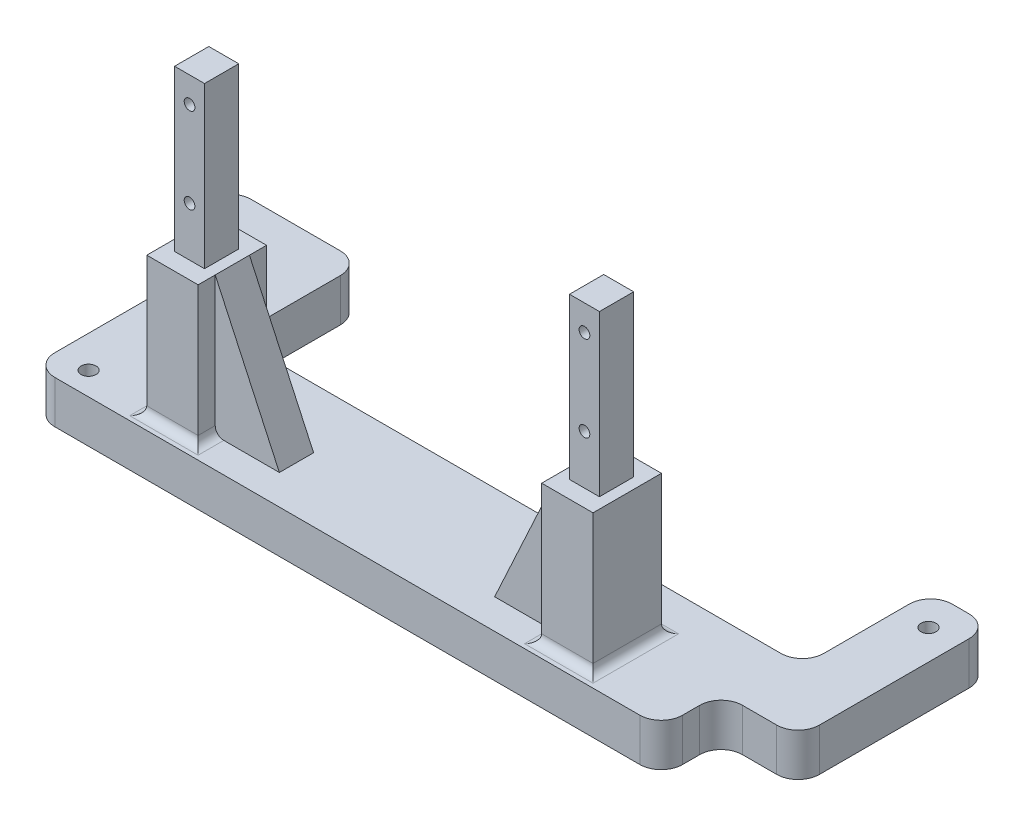
SolidWorks part; units mm, degrees
ref_plane "Front Plane" through (0, 0, 0) normal (0, 0, 1) x (1, 0, 0)
ref_plane "Top Plane" through (0, 0, 0) normal (0, 1, 0) x (1, 0, 0)
ref_plane "Right Plane" through (0, 0, 0) normal (1, 0, 0) x (0, 0, -1)
sketch "Sketch1" plane through (0, 0, 0) normal (0, 1, 0) x (1, 0, 0)
  line L0 (-7.5, -0.4) -> (-7.5, 38.6)
  line L1 (-7.5, 38.6) -> (-15.61, 38.6)
  line L2 (-20.61, 43.6) -> (-20.61, 48.6)
  line L4 (157.26, 48.6) -> (157.26, 13.6)
  line L14 (139.26, 3.6) -> (139.26, -0.4)
  line L18 (144.26, 8.6) -> (152.26, 8.6)
  line L20 (-2.5, -5.4) -> (134.26, -5.4)
  line L21 (-15.61, 53.6) -> (5.26, 53.6)
  line L22 (10.26, 48.6) -> (10.26, 28.6)
  line L23 (15.26, 23.6) -> (138.26, 23.6)
  line L24 (143.26, 28.6) -> (143.26, 48.6)
  line L25 (148.26, 53.6) -> (152.26, 53.6)
  circle A0 centre (0, 0) radius 1.75
  circle A1 centre (-14.61, 46.1) radius 1.75
  circle A3 centre (150.26, 46.1) radius 1.75
  arc A4 (138.26, 23.6) -> (143.26, 28.6) centre (138.26, 28.6) ccw
  arc A5 (143.26, 48.6) -> (148.26, 53.6) centre (148.26, 48.6) cw
  arc A6 (152.26, 53.6) -> (157.26, 48.6) centre (152.26, 48.6) cw
  arc A7 (157.26, 13.6) -> (152.26, 8.6) centre (152.26, 13.6) cw
  arc A8 (144.26, 8.6) -> (139.26, 3.6) centre (144.26, 3.6) ccw
  arc A9 (139.26, -0.4) -> (134.26, -5.4) centre (134.26, -0.4) cw
  arc A10 (-2.5, -5.4) -> (-7.5, -0.4) centre (-2.5, -0.4) cw
  arc A11 (15.26, 23.6) -> (10.26, 28.6) centre (15.26, 28.6) cw
  arc A12 (10.26, 48.6) -> (5.26, 53.6) centre (5.26, 48.6) ccw
  arc A13 (-20.61, 43.6) -> (-15.61, 38.6) centre (-15.61, 43.6) ccw
  arc A14 (-15.61, 53.6) -> (-20.61, 48.6) centre (-15.61, 48.6) ccw
  point P23 (-20.61, 46.1)
  point P27 (157.26, 8.6)
  point P32 (139.26, 8.6)
  point P43 (-20.61, 38.6)
  point P46 (-20.61, 53.6)
  dimension "D5" = 3.5
  dimension "D11" = 46.1
  dimension "D17" = 5
  dimension "D9" = 164.87
  dimension "D2" = 18
  dimension "D3" = 14.61
  dimension "D4" = 46.1
  dimension "D6" = 6
  dimension "D7" = 7
  dimension "D8" = 7.5
  dimension "D10" = 15
  dimension "D12" = 7
  dimension "D13" = 14
  dimension "D14" = 29
  dimension "D15" = 133
  dimension "D16" = 30
extrude "Boss-Extrude1" add sketch "Sketch1" along normal blind 10
sketch "Sketch3" plane through (0, 10, 0) normal (0, 1, 0) x (1, 0, 0)
  line L1 (18.5, 1.6) -> (25.5, 1.6)
  line L2 (18.5, 1.6) -> (18.5, 9.6)
  line L3 (18.5, 9.6) -> (25.5, 9.6)
  line L4 (25.5, 1.6) -> (25.5, 9.6)
  line L5 (110.82, 1.6) -> (117.82, 1.6)
  line L6 (110.82, 1.6) -> (110.82, 9.6)
  line L7 (110.82, 9.6) -> (117.82, 9.6)
  line L8 (117.82, 1.6) -> (117.82, 9.6)
  line L11 (-2.5, -5.4) -> (134.26, -5.4) construction
  line L12 (-7.5, 38.6) -> (-7.5, -0.4) construction
  point P8 (22, 9.6)
  point P9 (114.32, 9.6)
  dimension "D1" = 92.32
  dimension "D2" = 7
  dimension "D3" = 8
  dimension "D4" = 7
  dimension "D5" = 26
extrude "Boss-Extrude3" add sketch "Sketch3" along normal blind 70
sketch "Sketch4" plane through (0, 0, -9.6) normal (0, 0, -1) x (-1, 0, 0)
  line L0 (-25.5, 80) -> (-18.5, 80) construction
  line L1 (-117.82, 80) -> (-110.82, 80) construction
  circle A0 centre (-22, 74) radius 1.25
  circle A1 centre (-22, 54) radius 1.25
  circle A2 centre (-114.32, 54) radius 1.25
  circle A3 centre (-114.32, 74) radius 1.25
  point P10 (-22, 80)
  point P13 (-114.32, 80)
  dimension "D1" = 2.5
  dimension "D2" = 6
  dimension "D3" = 20
extrude "Cut-Extrude1" cut sketch "Sketch4" against normal up to next
sketch "Sketch5" plane through (0, 10, 0) normal (0, 1, 0) x (1, 0, 0)
  line L0 (18.5, 1.6) -> (25.5, 1.6) construction
  line L1 (16, 13.6) -> (28, 13.6)
  line L2 (16, 13.6) -> (16, -2.4)
  line L3 (16, -2.4) -> (28, -2.4)
  line L4 (28, 13.6) -> (28, -2.4)
  line L5 (108.32, 13.6) -> (120.32, 13.6)
  line L6 (108.32, 13.6) -> (108.32, -2.4)
  line L7 (108.32, -2.4) -> (120.32, -2.4)
  line L8 (120.32, 13.6) -> (120.32, -2.4)
  line L9 (25.5, 1.6) -> (25.5, 9.6) construction
  line L10 (110.82, 1.6) -> (117.82, 1.6) construction
  line L11 (117.82, 1.6) -> (117.82, 9.6) construction
  point P8 (22, -2.4)
  point P11 (22, 1.6)
  point P14 (25.5, 5.6)
  point P15 (28, 5.6)
  point P16 (114.32, -2.4)
  point P19 (114.32, 1.6)
  point P20 (120.32, 5.6)
  point P23 (117.82, 5.6)
  dimension "D1" = 12
  dimension "D2" = 16
extrude "Boss-Extrude4" add sketch "Sketch5" along normal blind 32.5
ref_plane "Plane1" through (22, 0, 0) normal (1, 0, 0) x (0, 0, -1)
ref_plane "Plane2" through (114.32, 0, 0) normal (-1, 0, 0) x (0, 0, 1)
ref_plane "Plane4" through (68.16, 0, 0) normal (1, 0, 0) x (0, 0, -1)
fillet "Fillet4" radius 2 8 edges at (108.32, 10, -5.6) (114.32, 10, 2.4) (28, 10, -5.6) (22, 10, 2.4) (16, 10, -5.6) (114.32, 10, -13.6) (22, 10, -13.6) (120.32, 10, -5.6)
ref_plane "Plane5" through (0, 0, -5.6) normal (0, 0, -1) x (-1, 0, 0)
sketch "Sketch6" plane through (0, 0, -5.6) normal (0, 0, -1) x (-1, 0, 0)
  line L0 (-108.32, 42.5) -> (-93.32, 10)
  line L1 (-106.32, 10) -> (-122.32, 10) construction
  dimension "D1" = 15
rib "Rib1" sketch "Sketch6" sketch "Sketch6" thickness 8 extrusion direction parallel to sketch draft on no parameters "D1"=8
mirror "Mirror1" about plane through (68.16, 0, 0) normal (1, 0, 0) of "Rib1"
